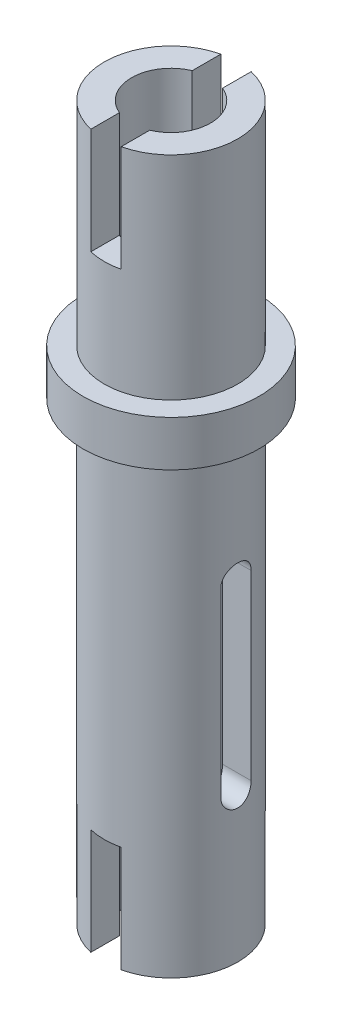
SolidWorks part; units mm, degrees
ref_plane "Front Plane" through (0, 0, 0) normal (0, 0, 1) x (1, 0, 0)
ref_plane "Top Plane" through (0, 0, 0) normal (0, 1, 0) x (1, 0, 0)
ref_plane "Right Plane" through (0, 0, 0) normal (1, 0, 0) x (0, 0, -1)
sketch "Sketch1" plane through (0, 0, 0) normal (0, 1, 0) x (1, 0, 0)
  circle A0 centre (0, 0) radius 2.2
  circle A1 centre (0, 0) radius 1.3
  dimension "D1" = 4.4
  dimension "D2" = 0.9
extrude "Boss-Extrude1" add sketch "Sketch1" along normal blind 23.5
ref_plane "Plane1" through (0, 16.5, 0) normal (0, 1, 0) x (1, 0, 0)
sketch "Sketch2" plane through (0, 16.5, 0) normal (0, 1, 0) x (1, 0, 0)
  circle A0 centre (0, 0) radius 2.2 construction
  circle A1 centre (0, 0) radius 2.2
  circle A2 centre (0, 0) radius 2.9
  dimension "D1" = 5.8
extrude "Boss-Extrude2" add sketch "Sketch2" against normal blind 1.5
sketch "Sketch4" plane through (0, 23.5, 0) normal (0, 1, 0) x (1, 0, 0)
  line L2 (-0.5, -2.1424) -> (-0.5, 2.1424)
  line L4 (0.5, -2.1424) -> (0.5, 2.1424)
  line L5 (-0.5, -2.1424) -> (0.5, 2.1424) construction
  line L6 (-0.5, 2.1424) -> (0.5, -2.1424) construction
  circle A0 centre (0, 0) radius 2.2 construction
  arc A1 (-0.5, -2.1424) -> (0.5, -2.1424) centre (0, 0) ccw
  circle A2 centre (0, 0) radius 1.3 construction
  circle A3 centre (0, 0) radius 1.3
  arc A4 (0.5, 2.1424) -> (-0.5, 2.1424) centre (0, 0) ccw
  point P6 (0, 0)
  point P11 (0, 0)
  point P12 (0, 0)
  point P13 (0, 0)
  point P14 (-0.8944, 2.01)
  circle M3 centre (0, 0) radius 2.2
  circle M4 centre (0, 0) radius 1.3
  dimension "D1" = 1
  dimension "D2" = 0.5
extrude "Cut-Extrude1" cut sketch "Sketch4" against normal blind 3.5 contours L4 L2 M3 M4 | L4 L2 M4 M3
sketch "Sketch5" plane through (0, 0, 0) normal (0, -1, 0) x (1, 0, 0)
  line L2 (-0.5, 2.1424) -> (-0.5, -2.1424)
  line L3 (0.5, -2.1424) -> (0.5, 2.1424)
  line L4 (-0.5, 2.1424) -> (-0.5, -2.1424)
  line L5 (0.5, -2.1424) -> (0.5, 2.1424)
  circle A1 centre (0, 0) radius 1.3
  circle A2 centre (0, 0) radius 1.3
  arc A4 (-0.5, -2.1424) -> (0.5, -2.1424) centre (0, 0) ccw
  arc A5 (0.5, 2.1424) -> (-0.5, 2.1424) centre (0, 0) ccw
  arc A6 (-0.5, -2.1424) -> (0.5, -2.1424) centre (0, 0) ccw
  arc A7 (0.5, 2.1424) -> (-0.5, 2.1424) centre (0, 0) ccw
  circle M6 centre (0, 0) radius 2.2
  circle M7 centre (0, 0) radius 1.3
  dimension "D1" = 0
  dimension "D2" = 0
extrude "Cut-Extrude2" cut sketch "Sketch5" against normal blind 3.5 contours L5 L4 M6 M7 | L5 L4 M7 M6
sketch "Sketch6" plane through (0, 0, 0) normal (1, 0, 0) x (0, 0, -1)
  line L0 (0, 10.9) -> (0, 4.9) construction
  line L1 (0.5, 10.9) -> (0.5, 4.9)
  line L2 (-0.5, 10.9) -> (-0.5, 4.9)
  arc A0 (0.5, 10.9) -> (-0.5, 10.9) centre (0, 10.9) ccw
  arc A1 (-0.5, 4.9) -> (0.5, 4.9) centre (0, 4.9) ccw
  point P3 (0, 7.9)
  dimension "D1" = 1
  dimension "D2" = 4.9
  dimension "D3" = 6
extrude "Cut-Extrude3" cut sketch "Sketch6" against normal mid plane 23.5
